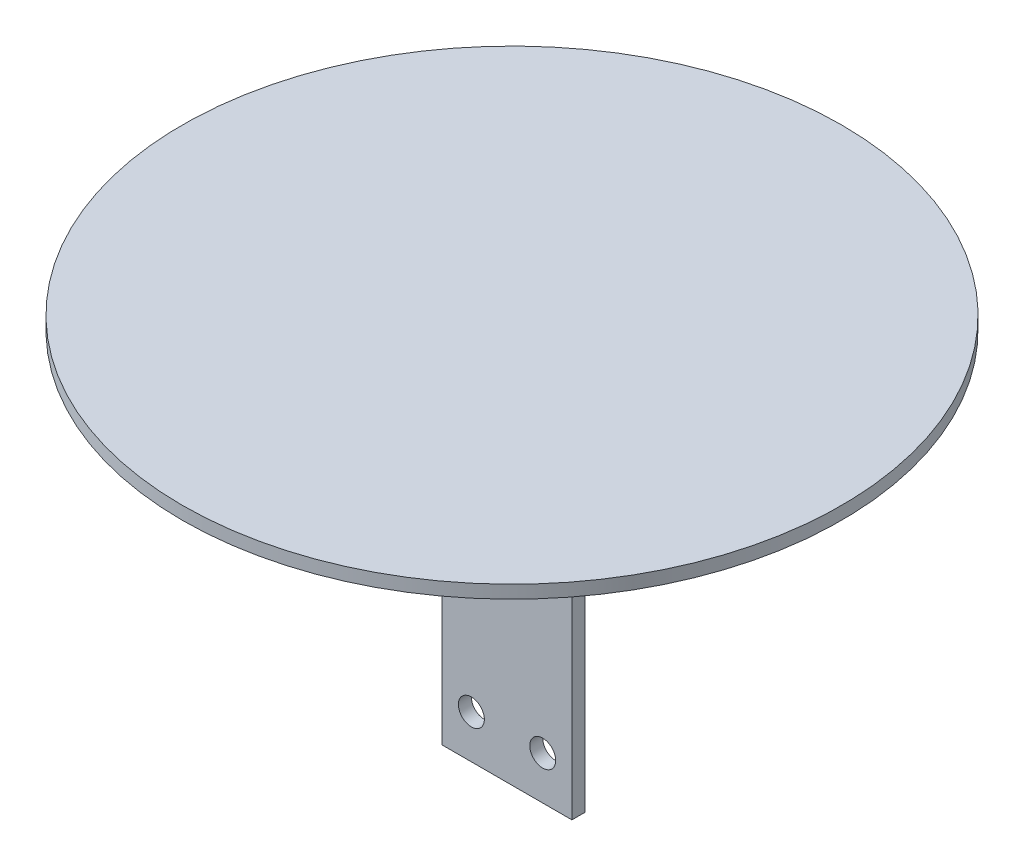
SolidWorks part; units mm, degrees
ref_plane "Front Plane" through (0, 0, 0) normal (0, 0, 1) x (1, 0, 0)
ref_plane "Top Plane" through (0, 0, 0) normal (0, 1, 0) x (1, 0, 0)
ref_plane "Right Plane" through (0, 0, 0) normal (1, 0, 0) x (0, 0, -1)
sketch "Sketch2" plane through (0, 0, 0) normal (0, 0, 1) x (1, 0, 0)
  line L0 (-8.25, 20) -> (8.25, 20) construction
  line L1 (-15, 45) -> (15, 45)
  line L2 (-15, 45) -> (-15, -45)
  line L3 (-15, -45) -> (15, -45)
  line L4 (15, 45) -> (15, -45)
  line L5 (-15, 45) -> (15, -45) construction
  line L6 (-15, -45) -> (15, 45) construction
  line L7 (8.25, 20) -> (0, 20) construction
  circle A0 centre (-8.25, 20) radius 3
  circle A1 centre (8.25, 20) radius 3
  circle A2 centre (-8.25, -35) radius 3
  circle A3 centre (8.25, -35) radius 3
  point P0 (0, 0)
  point P10 (0, 20)
  point P15 (0, 45)
  dimension "D3" = 6
  dimension "D4" = 6
  dimension "D8" = 6
  dimension "D9" = 6
  dimension "D1" = 30
  dimension "D2" = 90
  dimension "D5" = 16.5
  dimension "D6" = 55
  dimension "D7" = 25
extrude "Boss-Extrude1" add sketch "Sketch2" along normal blind 3
sketch "Sketch3" plane through (0, 45, 0) normal (0, 1, 0) x (1, 0, 0)
  circle A0 centre (0, -1.8553) radius 76.2
  dimension "D1" = 152.4
extrude "Boss-Extrude2" add sketch "Sketch3" along normal blind 3
sketch "Sketch4" plane through (15, 0, 0) normal (1, 0, 0) x (0, 0, -1)
  line L0 (-3, -45) -> (0, -45) construction
  line L1 (-21.5, 45) -> (18.5, 45)
  line L2 (-21.5, 45) -> (-21.5, 35)
  line L3 (-21.5, 35) -> (18.5, 35)
  line L4 (18.5, 45) -> (18.5, 35)
  point P5 (-1.5, 35)
  point P8 (-1.5, -45)
  dimension "D1" = 10
  dimension "D2" = 40
extrude "Boss-Extrude3" add sketch "Sketch4" against normal blind 3
sketch "Sketch5" plane through (-15, 0, 0) normal (-1, 0, 0) x (0, 0, 1)
  line L0 (3, 45) -> (0, 45) construction
  line L1 (-18.5, 45) -> (21.5, 45)
  line L2 (-18.5, 45) -> (-18.5, 35)
  line L3 (-18.5, 35) -> (21.5, 35)
  line L4 (21.5, 45) -> (21.5, 35)
  line L5 (3, -45) -> (0, -45) construction
  point P7 (1.5, 45)
  point P10 (1.5, -45)
  dimension "D1" = 40
  dimension "D2" = 10
extrude "Boss-Extrude4" add sketch "Sketch5" against normal blind 3
